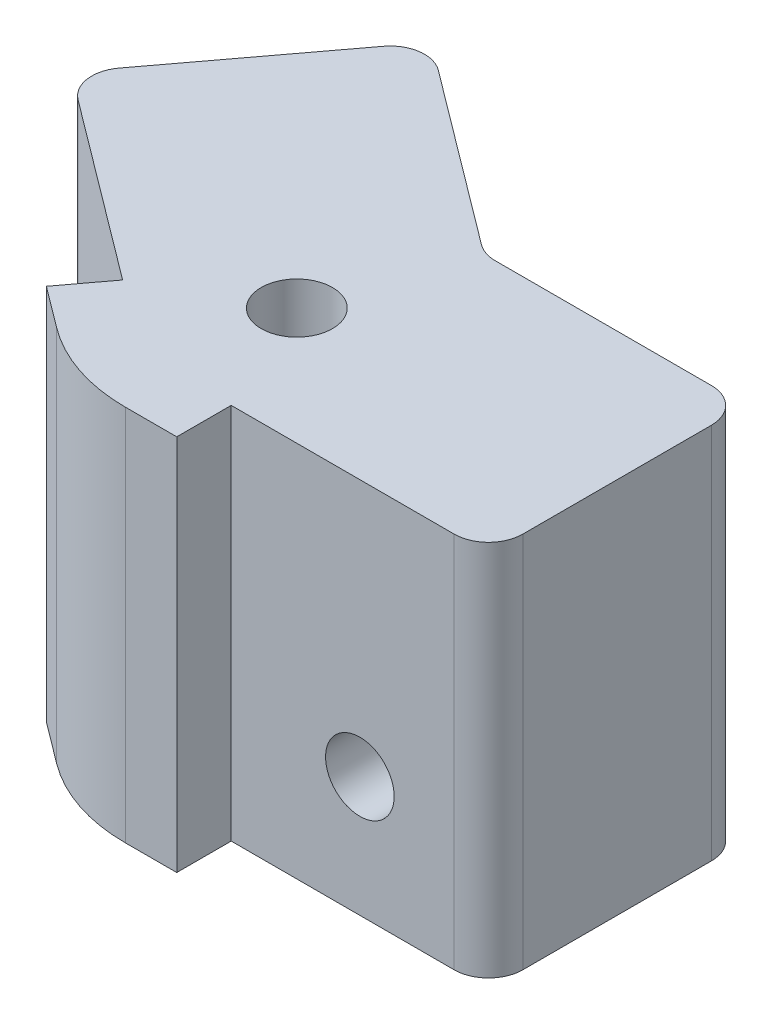
SolidWorks part; units mm, degrees
ref_plane "Front Plane" through (0, 0, 0) normal (0, 0, 1) x (1, 0, 0)
ref_plane "Top Plane" through (0, 0, 0) normal (0, 1, 0) x (1, 0, 0)
ref_plane "Right Plane" through (0, 0, 0) normal (1, 0, 0) x (0, 0, -1)
sketch "Sketch1" plane through (0, 0, 0) normal (0, 1, 0) x (1, 0, 0)
  line L0 (0, -10) -> (0, -6.825) construction
  line L2 (18, -6.825) -> (18, 54) construction
  line L3 (-6, -8) -> (-4.095, -5.46) construction
  line L5 (-18.495, 5.34) -> (18, 54) construction
  line L6 (-4.095, -5.46) -> (0, 0) construction
  line L8 (0, 0) -> (0, -6.825) construction
  line L9 (-3.1623, -9.4868) -> (0, 0) construction
  line L10 (0, 0) -> (18, 54) construction
  line L11 (-18.495, 5.34) -> (-9.495, 17.34)
  line L12 (-9.495, 17.34) -> (2.725, 8.175)
  line L13 (18, -6.825) -> (18, 8.175)
  line L14 (18, 8.175) -> (2.725, 8.175)
  line L15 (-6, -8) -> (-8.4, -6.2)
  line L16 (-8.4, -6.2) -> (-6.495, -3.66)
  line L17 (0, -10) -> (3, -10)
  line L18 (3, -10) -> (3, -6.825)
  line L19 (-18.495, 5.34) -> (-6.495, -3.66)
  line L20 (-6.495, -3.66) -> (-4.095, -5.46) construction
  line L21 (0, -6.825) -> (3, -6.825) construction
  line L22 (3, -6.825) -> (18, -6.825)
  line L23 (-6, -8) -> (-79.3333, 47) construction
  arc A0 (0, -10) -> (-6, -8) centre (0, 0) cw
  circle A1 centre (0, 0) radius 2.0788
  dimension "D1" = 10
  dimension "D3" = 4.1576
  dimension "D2" = 3.175
  dimension "D4" = 15
  dimension "D5" = 15
  dimension "D6" = 3
extrude "Boss-Extrude1" add sketch "Sketch1" along normal blind 70
sketch "Sketch2" plane through (0, 0, 6.825) normal (0, 0, 1) x (1, 0, 0)
  line L0 (10.5, 0) -> (10.5, 70) construction
  line L1 (3, 0) -> (18, 0) construction
  line L2 (3, 70) -> (18, 70) construction
  circle A0 centre (10.5, 15) radius 2
  circle A1 centre (10.5, 55) radius 2
  dimension "D1" = 4
  dimension "D2" = 15
  dimension "D3" = 15
extrude "Cut-Extrude1" cut sketch "Sketch2" against normal up to surface (15 mm away) up to face at (10.3625, 35, -8.175)
sketch "Sketch3" plane through (-4.095, 0, 5.46) normal (-0.6, 0, 0.8) x (0.8, 0, 0.6)
  line L0 (-10.5, 0) -> (-10.5, 70) construction
  line L1 (-18, 0) -> (-3, 0) construction
  line L2 (-18, 70) -> (-3, 70) construction
  circle A0 centre (-10.5, 15) radius 2
  circle A1 centre (-10.5, 55) radius 2
  dimension "D1" = 4
  dimension "D3" = 15
  dimension "D2" = 15
extrude "Cut-Extrude2" cut sketch "Sketch3" against normal up to surface (15 mm away) up to face at (-3.385, 35, -12.7575)
sketch "Sketch4" plane through (4.905, 0, -6.54) normal (0.6, 0, -0.8) x (-0.8, 0, -0.6)
  line L1 (10.5, 59.8714) -> (6.2812, 57.4357)
  line L2 (6.2812, 57.4357) -> (6.2813, 52.5643)
  line L3 (6.2813, 52.5643) -> (10.5, 50.1286)
  line L4 (10.5, 50.1286) -> (14.7188, 52.5643)
  line L5 (14.7188, 52.5643) -> (14.7187, 57.4357)
  line L6 (14.7187, 57.4357) -> (10.5, 59.8714)
  line L7 (10.5, 10.1286) -> (14.7188, 12.5643)
  line L8 (14.7188, 12.5643) -> (14.7188, 17.4357)
  line L9 (14.7188, 17.4357) -> (10.5, 19.8714)
  line L10 (10.5, 19.8714) -> (6.2813, 17.4357)
  line L11 (6.2813, 17.4357) -> (6.2813, 12.5643)
  line L12 (6.2813, 12.5643) -> (10.5, 10.1286)
  circle A0 centre (10.5, 55) radius 4.2188 construction
  circle A1 centre (10.5, 15) radius 4.2188 construction
  dimension "D1" = 8.4375
extrude "Cut-Extrude3" cut sketch "Sketch4" against normal blind 5
sketch "Sketch5" plane through (0, 0, -8.175) normal (0, 0, -1) x (-1, 0, 0)
  line L1 (-10.5, 50.1286) -> (-6.2813, 52.5643)
  line L2 (-6.2813, 52.5643) -> (-6.2813, 57.4357)
  line L3 (-6.2813, 57.4357) -> (-10.5, 59.8714)
  line L4 (-10.5, 59.8714) -> (-14.7188, 57.4357)
  line L5 (-14.7188, 57.4357) -> (-14.7188, 52.5643)
  line L6 (-14.7188, 52.5643) -> (-10.5, 50.1286)
  line L7 (-10.5, 10.1286) -> (-6.2813, 12.5643)
  line L8 (-6.2813, 12.5643) -> (-6.2813, 17.4357)
  line L9 (-6.2813, 17.4357) -> (-10.5, 19.8714)
  line L10 (-10.5, 19.8714) -> (-14.7188, 17.4357)
  line L11 (-14.7188, 17.4357) -> (-14.7188, 12.5643)
  line L12 (-14.7188, 12.5643) -> (-10.5, 10.1286)
  circle A0 centre (-10.5, 55) radius 4.2188 construction
  circle A1 centre (-10.5, 15) radius 4.2188 construction
  dimension "D1" = 8.4375
extrude "Cut-Extrude4" cut sketch "Sketch5" against normal blind 5
ref_plane "Plane1" through (4.2525, 0, -12.7575) normal (0.3162, 0, -0.9487) x (-0.9487, 0, -0.3162)
sketch "Sketch7" plane through (0, 70, 0) normal (0, 1, 0) x (1, 0, 0)
  line L0 (0, 0) -> (2.725, 8.175) construction
  line L1 (-1.5409, -4.6228) -> (3.233, -3.6459) construction
  line L2 (3.233, -3.6459) -> (4.7739, 0.9769) construction
  line L3 (4.7739, 0.9769) -> (1.5409, 4.6228) construction
  line L4 (1.5409, 4.6228) -> (-3.233, 3.6459) construction
  line L5 (-3.233, 3.6459) -> (-4.7739, -0.9769) construction
  line L6 (-4.7739, -0.9769) -> (-1.5409, -4.6228) construction
  line L7 (-4.7739, -0.9769) -> (-0.8336, 10.844)
  line L8 (2.725, 8.175) -> (-9.495, 17.34) construction
  line L9 (3.233, -3.6459) -> (7.1733, 8.175)
  line L10 (18, 8.175) -> (2.725, 8.175) construction
  line L11 (-4.7739, -0.9769) -> (-1.5409, -4.6228)
  line L12 (-1.5409, -4.6228) -> (3.233, -3.6459)
  line L13 (-0.8336, 10.844) -> (2.725, 8.175)
  line L14 (2.725, 8.175) -> (7.1733, 8.175)
  circle A0 centre (0, 0) radius 4.22 construction
  dimension "D1" = 8.44
extrude "Cut-Extrude5" cut sketch "Sketch7" along direction (0, -1, 0) on the side against the normal blind 5 from offset 5 offset against normal yes
fillet "Fillet1" radius 2 6 edges at (2.725, 67.5, -8.175) (18, 35, 6.825) (18, 35, -8.175) (2.725, 30, -8.175) (-9.495, 35, -17.34) (-18.495, 35, -5.34)
sketch "Sketch8" plane through (0, 0, 0) normal (0, -1, 0) x (1, 0, 0)
  line L1 (-20.4741, -19.7995) -> (22.4461, -19.7995)
  line L2 (-20.4741, -19.7995) -> (-20.4741, 13.0505)
  line L3 (-20.4741, 13.0505) -> (22.4461, 13.0505)
  line L4 (22.4461, -19.7995) -> (22.4461, 13.0505)
  point P4 (-20.4741, -19.7995)
extrude "Cut-Extrude6" cut sketch "Sketch8" against normal blind 48
